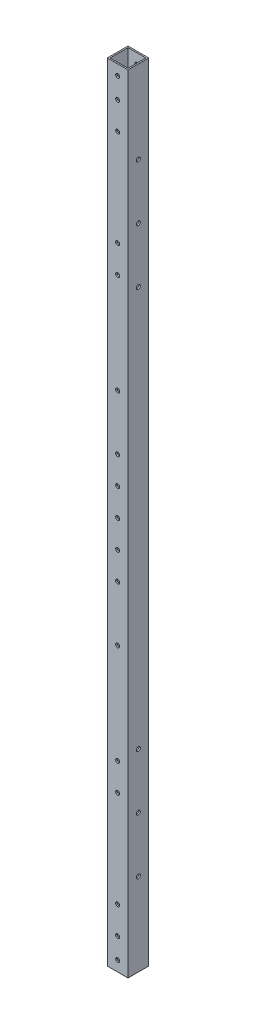
SolidWorks part; units mm, degrees
material "Thornel Mat VMA"
ref_plane "前视基准面" through (0, 0, 0) normal (0, 0, 1) x (1, 0, 0)
ref_plane "上视基准面" through (0, 0, 0) normal (0, 1, 0) x (1, 0, 0)
ref_plane "右视基准面" through (0, 0, 0) normal (1, 0, 0) x (0, 0, -1)
sketch "草图1" plane through (0, 0, 0) normal (0, 1, 0) x (1, 0, 0)
  line L1 (-7.5, -7.5) -> (7.5, -7.5)
  line L2 (-7.5, -7.5) -> (-7.5, 7.5)
  line L3 (-7.5, 7.5) -> (7.5, 7.5)
  line L4 (7.5, -7.5) -> (7.5, 7.5)
  line L5 (-7.5, -7.5) -> (7.5, 7.5) construction
  line L6 (-7.5, 7.5) -> (7.5, -7.5) construction
  point P0 (0, 0)
  dimension "D1" = 15
  dimension "D2" = 15
extrude "拉伸-薄壁1" add sketch "草图1" along normal blind 570 thin thin type one direction reverse wall 1
sketch "草图2" plane through (0, 0, 0) normal (0, 0, 1) x (1, 0, 0)
  line L0 (0, 0) -> (0, 570) construction
  line L1 (-7.5, 570) -> (7.5, 570) construction
  line L2 (-1000, 285) -> (49000, 285) construction
  line L3 (-7.5, 0) -> (7.5, 0) construction
  circle A0 centre (0, 7.5) radius 1.45
  circle A1 centre (0, 22.5) radius 1.45
  circle A2 centre (0, 42.5) radius 1.45
  circle A3 centre (0, 527.5) radius 1.45
  circle A4 centre (0, 547.5) radius 1.45
  circle A5 centre (0, 562.5) radius 1.45
  circle A6 centre (0, 285) radius 1.45
  circle A7 centre (0, 305) radius 1.45
  circle A8 centre (0, 265) radius 1.45
  circle A9 centre (0, 112.5) radius 1.45
  circle A10 centre (0, 132.5) radius 1.45
  circle A11 centre (0, 437.5) radius 1.45
  circle A12 centre (0, 457.5) radius 1.45
  circle A13 centre (0, 245) radius 1.45
  circle A14 centre (0, 205) radius 1.45
  circle A15 centre (0, 365) radius 1.45
  circle A16 centre (0, 325) radius 1.45
  point P14 (0, 285)
  dimension "D1" = 2.9
  dimension "D5" = 2.9
  dimension "D8" = 70
  dimension "D9" = 20
  dimension "D2" = 7.5
  dimension "D3" = 15
  dimension "D4" = 20
  dimension "D6" = 20
  dimension "D7" = 20
  dimension "D10" = 40
  dimension "D11" = 40
extrude "切除-拉伸1" cut sketch "草图2" against normal through all and the other way blind 10
sketch "草图3" plane through (7.5, 0, 0) normal (1, 0, 0) x (0, 0, -1)
  line L0 (0, 0) -> (0, 570) construction
  line L1 (-7.5, 570) -> (7.5, 570) construction
  line L2 (-7.5, 0) -> (7.5, 0) construction
  line L3 (-1000, 285) -> (49000, 285) construction
  circle A0 centre (0, 60) radius 1.45
  circle A1 centre (0, 100) radius 1.45
  circle A2 centre (0, 470) radius 1.45
  circle A3 centre (0, 510) radius 1.45
  circle A4 centre (0, 140) radius 1.45
  circle A5 centre (0, 430) radius 1.45
  point P14 (0, 285)
  dimension "D1" = 2.9
  dimension "D4" = 40
  dimension "D2" = 60
  dimension "D3" = 40
extrude "切除-拉伸2" cut sketch "草图3" against normal through all
